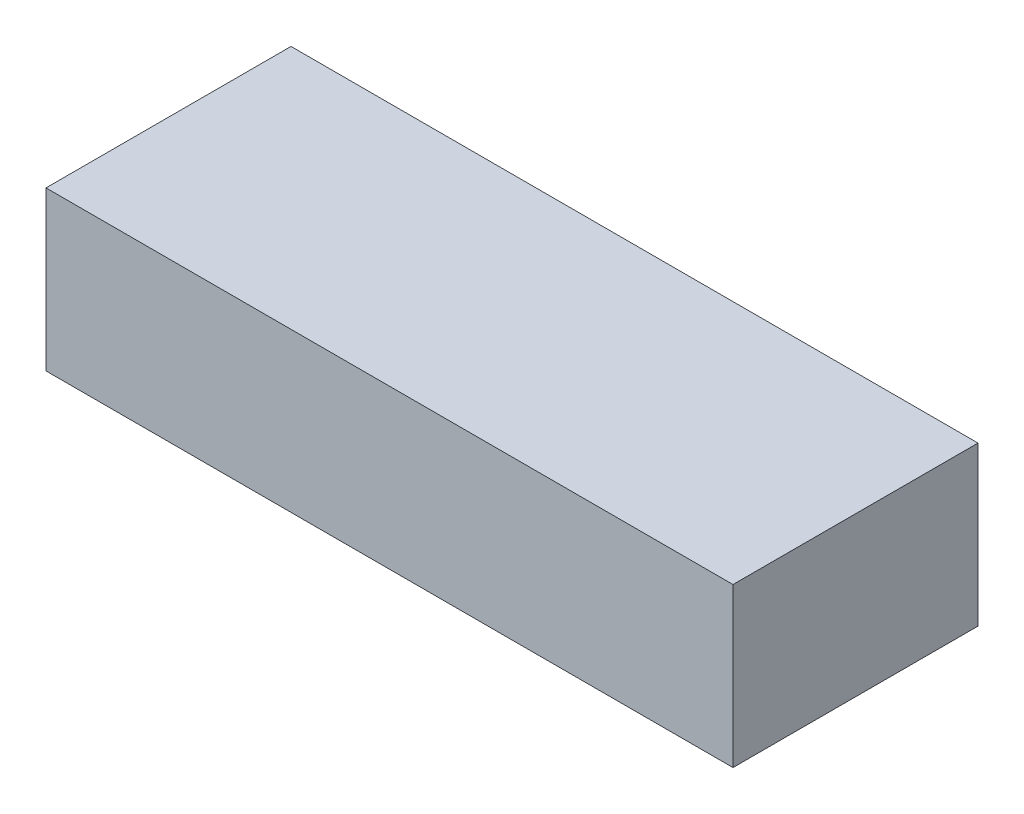
SolidWorks part; units mm, degrees
ref_plane "Front Plane" through (0, 0, 0) normal (0, 0, 1) x (1, 0, 0)
ref_plane "Top Plane" through (0, 0, 0) normal (0, 1, 0) x (1, 0, 0)
ref_plane "Right Plane" through (0, 0, 0) normal (1, 0, 0) x (0, 0, -1)
sketch "Sketch1" plane through (0, 0, 0) normal (0, 1, 0) x (1, 0, 0)
  line L1 (71.5, -25.5) -> (-71.5, -25.5)
  line L2 (71.5, -25.5) -> (71.5, 25.5)
  line L3 (71.5, 25.5) -> (-71.5, 25.5)
  line L4 (-71.5, -25.5) -> (-71.5, 25.5)
  line L5 (71.5, -25.5) -> (-71.5, 25.5) construction
  line L6 (71.5, 25.5) -> (-71.5, -25.5) construction
  point P0 (0, 0)
  dimension "D1" = 143
  dimension "D2" = 51
extrude "Boss-Extrude1" add sketch "Sketch1" along normal blind 33
ref_plane "Plane1" through (0, 16.5, 0) normal (0, 1, 0) x (1, 0, 0)
